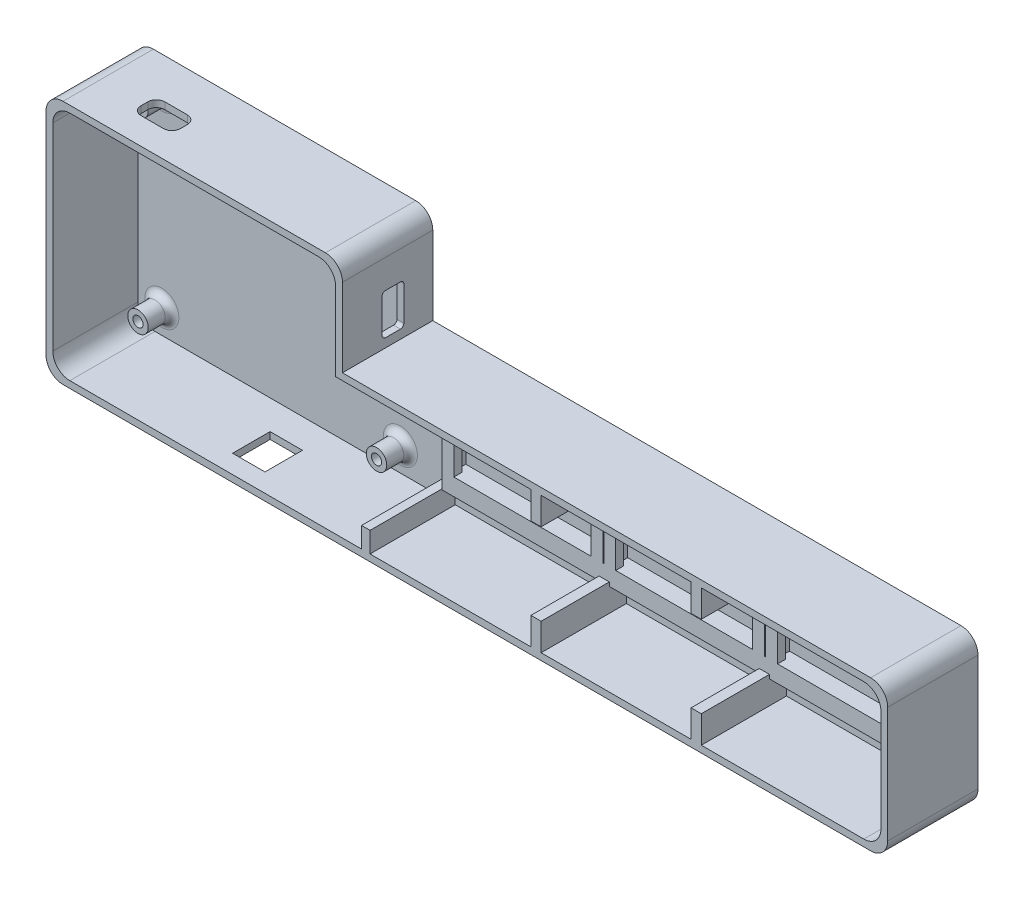
SolidWorks part; units mm, degrees
ref_plane "前视基准面" through (0, 0, 0) normal (0, 0, 1) x (1, 0, 0)
ref_plane "上视基准面" through (0, 0, 0) normal (0, 1, 0) x (1, 0, 0)
ref_plane "右视基准面" through (0, 0, 0) normal (1, 0, 0) x (0, 0, -1)
sketch "草图1" plane through (0, 0, 0) normal (0, 0, 1) x (1, 0, 0)
  line L1 (104.0535, -78.1263) -> (-4.5381, -78.1263)
  line L2 (82.4619, -34.1263) -> (82.4619, -6.1263)
  line L3 (82.4619, -6.1263) -> (-4.5381, -6.1263)
  line L4 (-4.5381, -78.1263) -> (-4.5381, -6.1263)
  line L5 (104.0535, -78.1263) -> (-4.5381, -6.1263) construction
  line L6 (82.4619, -6.1263) -> (-4.5381, -78.1263) construction
  line L14 (4.4619, -9.1263) -> (74.4619, -9.1263) construction
  line L16 (-0.5381, -69.1263) -> (-0.5381, -14.1263) construction
  line L17 (74.4619, -74.1263) -> (4.4619, -74.1263) construction
  line L18 (79.4619, -14.1263) -> (79.4619, -20.1113) construction
  line L19 (82.4619, -34.1263) -> (242.4619, -34.1263)
  line L20 (104.0535, -78.1263) -> (242.4619, -78.1263)
  line L21 (242.4619, -78.1263) -> (242.4619, -34.1263)
  point P0 (43.7639, -38.1522)
  dimension "D1" = 3
  dimension "D2" = 3
  dimension "D3" = 4
  dimension "D4" = 4
  dimension "D5" = 160
  dimension "D6" = 44
extrude "凸台-拉伸1" add sketch "草图1" along normal blind 1.5
sketch "草图2" plane through (0, 0, 1.5) normal (0, 0, 1) x (1, 0, 0)
  line L0 (80.4619, -8.1263) -> (-2.5381, -8.1263)
  line L1 (-2.5381, -8.1263) -> (-2.5381, -76.1263)
  line L2 (-2.5381, -76.1263) -> (240.4619, -76.1263)
  line L3 (240.4619, -76.1263) -> (240.4619, -36.1263)
  line L4 (240.4619, -36.1263) -> (80.4619, -36.1263)
  line L5 (80.4619, -36.1263) -> (80.4619, -8.1263)
  line L6 (-4.5381, -6.1263) -> (-4.5381, -78.1263)
  line L7 (-4.5381, -78.1263) -> (242.4619, -78.1263)
  line L8 (242.4619, -78.1263) -> (242.4619, -34.1263)
  line L9 (242.4619, -34.1263) -> (82.4619, -34.1263)
  line L10 (82.4619, -34.1263) -> (82.4619, -6.1263)
  line L11 (82.4619, -6.1263) -> (-4.5381, -6.1263)
  line L12 (-4.5381, -6.1263) -> (-4.5381, -78.1263)
  line L13 (-4.5381, -78.1263) -> (242.4619, -78.1263)
  line L14 (242.4619, -78.1263) -> (242.4619, -34.1263)
  line L15 (242.4619, -34.1263) -> (82.4619, -34.1263)
  line L16 (82.4619, -34.1263) -> (82.4619, -6.1263)
  line L17 (82.4619, -6.1263) -> (-4.5381, -6.1263)
  dimension "D1" = 0
  dimension "D2" = 2
extrude "凸台-拉伸2" add sketch "草图2" along normal blind 25
fillet "圆角1" radius 5 10 edges at (242.4619, -34.1263, 13.25) (240.4619, -36.1263, 14) (240.4619, -76.1263, 14) (242.4619, -78.1263, 13.25) (-4.5381, -78.1263, 13.25) (-2.5381, -76.1263, 14) (82.4619, -6.1263, 13.25) (80.4619, -8.1263, 14) (-2.5381, -8.1263, 14) (-4.5381, -6.1263, 13.25)
sketch "草图3" plane through (0, 0, 1.5) normal (0, 0, 1) x (1, 0, 0)
  circle A0 centre (74.4618, -14.1263) radius 3
  circle A1 centre (74.4618, -14.1263) radius 1.5
  circle A2 centre (4.4618, -14.1263) radius 1.5
  circle A3 centre (4.4618, -14.1263) radius 3
  circle A4 centre (4.4618, -69.1263) radius 1.5
  circle A5 centre (4.4618, -69.1263) radius 3
  circle A6 centre (74.4618, -69.1263) radius 1.5
  circle A7 centre (74.4618, -69.1263) radius 3
  dimension "D1" = 2
  dimension "D2" = 2
extrude "凸台-拉伸3" add sketch "草图3" along normal blind 7
fillet "圆角2" radius 2 4 edges at (77.4618, -14.1263, 1.5) (77.4618, -69.1263, 1.5) (7.4618, -69.1263, 1.5) (7.4618, -14.1263, 1.5)
sketch "草图4" plane through (82.4619, 0, 0) normal (1, 0, 0) x (0, 0, -1)
  line L0 (-11.6915, -28.5263) -> (-11.6915, -22.5263) construction
  line L1 (-14.8829, -31.5263) -> (-8.5, -31.5263)
  line L2 (-14.8829, -31.5263) -> (-14.8829, -19.5263)
  line L3 (-14.8829, -19.5263) -> (-8.5, -19.5263)
  line L4 (-8.5, -31.5263) -> (-8.5, -19.5263)
  line L5 (-14.8829, -31.5263) -> (-8.5, -19.5263) construction
  line L6 (-14.8829, -19.5263) -> (-8.5, -31.5263) construction
  point P0 (-11.6915, -25.5263)
extrude "切除-拉伸1" cut sketch "草图4" against normal up to next
fillet "圆角3" radius 1 4 edges at (81.4619, -19.5263, 14.8829) (81.4619, -31.5263, 14.8829) (81.4619, -31.5263, 8.5) (81.4619, -19.5263, 8.5)
sketch "草图5" plane through (0, -6.1263, 0) normal (0, 1, 0) x (1, 0, 0)
  line L0 (11.1943, -8.5) -> (26.4728, -8.5) construction
  line L1 (4.4619, -8.5) -> (74.4619, -8.5) construction
  line L3 (14.0336, -17.2) -> (23.6336, -17.2) construction
  line L4 (14.0336, -17.2) -> (14.0336, -13.2) construction
  line L5 (14.0336, -13.2) -> (23.6336, -13.2) construction
  line L6 (23.6336, -17.2) -> (23.6336, -13.2) construction
  line L7 (14.0336, -17.2) -> (23.6336, -13.2) construction
  line L8 (14.0336, -13.2) -> (23.6336, -17.2) construction
  line L12 (13.0336, -18.7) -> (24.6336, -18.7)
  line L13 (13.0336, -18.7) -> (13.0336, -11.7)
  line L14 (13.0336, -11.7) -> (24.6336, -11.7)
  line L15 (24.6336, -18.7) -> (24.6336, -11.7)
  line L16 (13.0336, -18.7) -> (24.6336, -11.7) construction
  line L17 (13.0336, -11.7) -> (24.6336, -18.7) construction
  point P5 (18.8336, -15.2)
  point P10 (18.8336, -15.2)
  point P16 (18.8336, -8.5)
  dimension "D1" = 6.7
  dimension "D2" = 4
  dimension "D3" = 9.6
  dimension "D4" = 11.6
  dimension "D5" = 7
extrude "切除-拉伸2" cut sketch "草图5" against normal up to next
fillet "圆角4" radius 2.5 4 edges at (13.0336, -7.1263, 11.7) (13.0336, -7.1263, 18.7) (24.6336, -7.1263, 18.7) (24.6336, -7.1263, 11.7)
sketch "草图6" plane through (0, 0, 1.5) normal (0, 0, 1) x (1, 0, 0)
  line L0 (235.4619, -36.1263) -> (80.4619, -36.1263) construction
  line L1 (236.646, -47.9763) -> (91.646, -47.9763)
  line L2 (236.646, -47.9763) -> (236.646, -42.9763)
  line L3 (236.646, -42.9763) -> (91.646, -42.9763)
  line L4 (91.646, -47.9763) -> (91.646, -42.9763)
  line L5 (236.646, -47.9763) -> (91.646, -42.9763) construction
  line L6 (236.646, -42.9763) -> (91.646, -47.9763) construction
  line L7 (2.4619, -76.1263) -> (235.4619, -76.1263) construction
  line L8 (236.646, -69.2763) -> (91.646, -69.2763)
  line L9 (236.646, -69.2763) -> (236.646, -64.2763)
  line L10 (236.646, -64.2763) -> (91.646, -64.2763)
  line L11 (91.646, -69.2763) -> (91.646, -64.2763)
  line L12 (236.646, -69.2763) -> (91.646, -64.2763) construction
  line L13 (236.646, -64.2763) -> (91.646, -69.2763) construction
  point P0 (164.146, -45.4763)
  point P7 (164.146, -66.7763)
  dimension "D1" = 5
  dimension "D2" = 11.85
  dimension "D3" = 145
  dimension "D4" = 5
  dimension "D5" = 11.85
  dimension "D6" = 145
extrude "凸台-拉伸4" add sketch "草图6" along normal blind 5
sketch "草图7" plane through (0, -47.9763, 0) normal (0, -1, 0) x (1, 0, 0)
  line L0 (91.646, 6.5) -> (95.146, 6.5)
  line L1 (91.646, 6.5) -> (236.646, 6.5) construction
  line L2 (95.146, 6.5) -> (95.146, 4.15)
  line L3 (95.146, 4.15) -> (93.646, 4.15)
  line L4 (93.646, 4.15) -> (93.646, 1.5)
  line L5 (2.4619, 1.5) -> (235.4619, 1.5) construction
  line L6 (93.646, 1.5) -> (91.646, 1.5)
  line L7 (91.646, 1.5) -> (91.646, 6.5)
  line L8 (115.246, -6.8376) -> (115.246, 48.0874) construction
  line L9 (138.846, 1.5) -> (138.846, 6.5)
  line L10 (136.846, 1.5) -> (138.846, 1.5)
  line L11 (136.846, 4.15) -> (136.846, 1.5)
  line L12 (135.346, 4.15) -> (136.846, 4.15)
  line L13 (135.346, 6.5) -> (135.346, 4.15)
  line L14 (138.846, 6.5) -> (135.346, 6.5)
  line L15 (139.146, 1.5) -> (139.146, 6.5)
  line L16 (139.146, 6.5) -> (142.646, 6.5)
  line L17 (142.646, 6.5) -> (142.646, 4.15)
  line L18 (142.646, 4.15) -> (141.146, 4.15)
  line L19 (141.146, 4.15) -> (141.146, 1.5)
  line L20 (141.146, 1.5) -> (139.146, 1.5)
  line L21 (186.346, 1.5) -> (186.346, 6.5)
  line L22 (186.346, 6.5) -> (182.846, 6.5)
  line L23 (182.846, 6.5) -> (182.846, 4.15)
  line L24 (182.846, 4.15) -> (184.346, 4.15)
  line L25 (184.346, 4.15) -> (184.346, 1.5)
  line L26 (184.346, 1.5) -> (186.346, 1.5)
  line L27 (186.646, 1.5) -> (186.646, 6.5)
  line L28 (186.646, 6.5) -> (190.146, 6.5)
  line L29 (190.146, 6.5) -> (190.146, 4.15)
  line L30 (190.146, 4.15) -> (188.646, 4.15)
  line L31 (188.646, 4.15) -> (188.646, 1.5)
  line L32 (188.646, 1.5) -> (186.646, 1.5)
  line L33 (233.846, 1.5) -> (233.846, 6.5)
  line L34 (233.846, 6.5) -> (230.346, 6.5)
  line L35 (230.346, 6.5) -> (230.346, 4.15)
  line L36 (230.346, 4.15) -> (231.846, 4.15)
  line L37 (231.846, 4.15) -> (231.846, 1.5)
  line L38 (231.846, 1.5) -> (233.846, 1.5)
  dimension "D1" = 3.5
  dimension "D2" = 2.35
  dimension "D3" = 1.5
  dimension "D4" = 21.6
  dimension "D5" = 3
extrude "凸台-拉伸5" add sketch "草图7" along normal up to next
sketch "草图8" plane through (0, -78.1263, 0) normal (0, -1, 0) x (1, 0, 0)
  line L0 (49.542, 13.3914) -> (49.542, 17.0914) construction
  line L1 (44.792, 10.0702) -> (54.292, 10.0702)
  line L2 (44.792, 10.0702) -> (44.792, 21.0702)
  line L3 (44.792, 21.0702) -> (54.292, 21.0702)
  line L4 (54.292, 10.0702) -> (54.292, 21.0702)
  line L5 (44.792, 10.0702) -> (54.292, 21.0702) construction
  line L6 (44.792, 21.0702) -> (54.292, 10.0702) construction
  line L8 (49.542, 15.5702) -> (49.542, 7.1382) construction
  point P0 (49.542, 15.5702)
extrude "切除-拉伸3" cut sketch "草图8" against normal up to next
sketch "草图9" plane through (0, 0, 1.5) normal (0, 0, 1) x (1, 0, 0)
  line L0 (235.4619, -36.1263) -> (80.4619, -36.1263) construction
  line L1 (137.7603, -44.1263) -> (140.7603, -44.1263)
  line L2 (137.7603, -44.1263) -> (137.7603, -36.1263)
  line L3 (137.7603, -36.1263) -> (140.7603, -36.1263)
  line L4 (140.7603, -44.1263) -> (140.7603, -36.1263)
  line L5 (137.7603, -44.1263) -> (140.7603, -36.1263) construction
  line L6 (137.7603, -36.1263) -> (140.7603, -44.1263) construction
  line L7 (240.4619, -56.1263) -> (91.646, -56.1263) construction
  line L8 (240.4619, -71.1263) -> (240.4619, -41.1263) construction
  line L9 (91.646, -42.9763) -> (91.646, -69.2763) construction
  line L10 (137.7603, -68.1263) -> (140.7603, -68.1263)
  line L11 (140.7603, -68.1263) -> (140.7603, -76.1263)
  line L12 (137.7603, -68.1263) -> (137.7603, -76.1263)
  line L13 (137.7603, -76.1263) -> (140.7603, -76.1263)
  line L14 (184.7603, -44.1263) -> (184.7603, -36.1263)
  line L15 (184.7603, -44.1263) -> (187.7603, -44.1263)
  line L16 (187.7603, -44.1263) -> (187.7603, -36.1263)
  line L17 (184.7603, -36.1263) -> (187.7603, -36.1263)
  line L18 (184.7603, -68.1263) -> (187.7603, -68.1263)
  line L19 (187.7603, -68.1263) -> (187.7603, -76.1263)
  line L20 (184.7603, -76.1263) -> (187.7603, -76.1263)
  line L21 (184.7603, -68.1263) -> (184.7603, -76.1263)
  line L22 (2.4619, -76.1263) -> (235.4619, -76.1263) construction
  line L23 (88.0517, -70.1263) -> (90.5517, -70.1263)
  line L24 (88.0517, -70.1263) -> (88.0517, -76.1263)
  line L25 (88.0517, -76.1263) -> (90.5517, -76.1263)
  line L26 (90.5517, -70.1263) -> (90.5517, -76.1263)
  line L27 (88.0517, -70.1263) -> (90.5517, -76.1263) construction
  line L28 (88.0517, -76.1263) -> (90.5517, -70.1263) construction
  point P0 (139.2603, -40.1263)
  point P17 (89.3017, -73.1263)
  dimension "D1" = 3
  dimension "D2" = 8
  dimension "D4" = 6
  dimension "D5" = 2.5
  dimension "D3" = 2
extrude "凸台-拉伸6" add sketch "草图9" along normal blind 25
